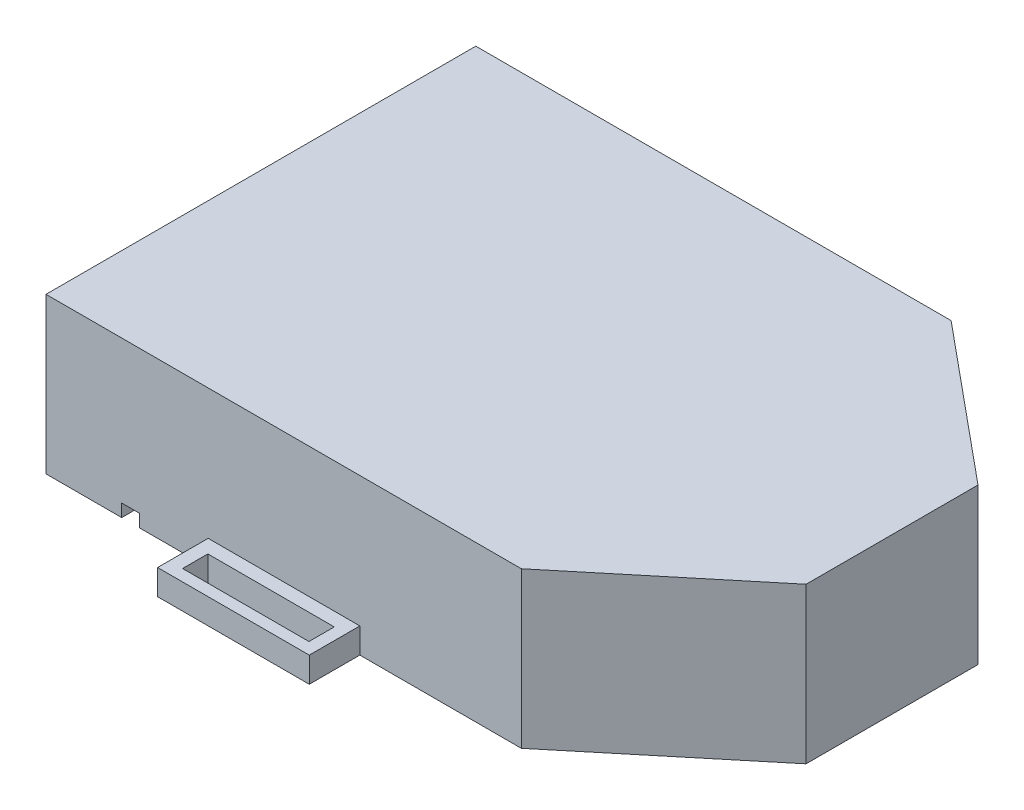
SolidWorks part; units mm, degrees
ref_plane "Front Plane" through (0, 0, 0) normal (0, 0, 1) x (1, 0, 0)
ref_plane "Top Plane" through (0, 0, 0) normal (0, 1, 0) x (1, 0, 0)
ref_plane "Right Plane" through (0, 0, 0) normal (1, 0, 0) x (0, 0, -1)
sketch "Sketch1" plane through (0, 0, 0) normal (1, 0, 0) x (0, 0, -1)
  line L23 (-43, -17.5) -> (42, -17.5)
  line L28 (-43, -17.5) -> (-43, 17.5)
  line L29 (-43, 17.5) -> (42, 17.5)
  line L30 (42, -17.5) -> (42, 17.5)
  point P0 (0, 0)
  dimension "D1" = 35
  dimension "D2" = 85
extrude "Boss-Extrude1" add sketch "Sketch1" along normal blind 145.5
sketch "Sketch4" plane through (0, 0, 0) normal (-1, 0, 0) x (0, 0, 1)
  circle A0 centre (0, 0) radius 12.75
  dimension "D1" = 25.5
extrude "Cut-Extrude2" cut sketch "Sketch4" against normal blind 55
sketch "Sketch9" plane through (0, 17.5, 0) normal (0, 1, 0) x (1, 0, 0)
  line L0 (0, 42) -> (0, -43)
  line L1 (0, -43) -> (94, -43)
  line L2 (145.5, -43) -> (0, -43) construction
  line L3 (94, -43) -> (124.818, -17.5)
  line L4 (124.818, -17.5) -> (124.818, 16.5)
  line L5 (124.818, 16.5) -> (94, 42)
  line L6 (145.5, 42) -> (0, 42) construction
  line L7 (94, 42) -> (0, 42)
  line L8 (94, 42) -> (145.5, 42)
  line L9 (145.5, 42) -> (145.5, -43)
  line L10 (145.5, -43) -> (94, -43)
  line M8 (0, -43) -> (145.5, -43)
  line M9 (145.5, -43) -> (145.5, 42)
  line M10 (145.5, 42) -> (0, 42)
  dimension "D1" = 94
  dimension "D2" = 94
  dimension "D3" = 34
  dimension "D4" = 40
  dimension "44" = 40
extrude "Cut-Extrude3" cut sketch "Sketch9" against normal through all contours L5 L4 L3 M8 M9 M10
sketch "Sketch11" plane through (0, -17.5, 0) normal (0, -1, 0) x (1, 0, 0)
  line L0 (0, -12.75) -> (55, -12.75) construction
  line L1 (55, 12.75) -> (43, 12.75)
  line L2 (55, 12.75) -> (55, -12.75)
  line L3 (55, -12.75) -> (43, -12.75)
  line L4 (43, 12.75) -> (43, -12.75)
  dimension "D1" = 12
extrude "Cut-Extrude5" cut sketch "Sketch11" against normal blind 10
sketch "Sketch12" plane through (0, -17.5, 0) normal (0, -1, 0) x (1, 0, 0)
  line L7 (48.7846, 39.5274) -> (18.4738, 39.5274)
  line L12 (94, 43) -> (0, 43) construction
  line L14 (47.4745, 10.9894) -> (50.9745, 10.9894)
  line L15 (47.4745, 36.0861) -> (14.9738, 36.0861)
  line L16 (47.4745, 10.9894) -> (47.4745, 36.0861)
  line L18 (50.9745, 10.9894) -> (50.9745, 39.5274)
  line L21 (14.9738, 39.5274) -> (14.9738, 36.0861)
  line L23 (14.9738, 39.5274) -> (14.9738, 43)
  line L24 (14.9738, 43) -> (18.4738, 43)
  line L25 (18.4738, 39.5274) -> (18.4738, 43)
  line L26 (50.9745, 36.0861) -> (50.9745, 39.5274)
  line L27 (50.9745, 39.5274) -> (48.7846, 39.5274)
  point P0 (21.5, 0)
  point P7 (49, 26.1387)
  line M8 (43, 12.75) -> (55, 12.75)
  line M15 (94, 43) -> (0, 43)
  dimension "D1" = 3.5
extrude "Cut-Extrude6" cut sketch "Sketch12" against normal blind 2.5 contours L18 L27 L7 L25 L23 L21 L15 L16 M15 M8
sketch "Sketch14" plane through (0, -17.5, 0) normal (0, -1, 0) x (1, 0, 0)
  line L0 (0, 0.5) -> (124.818, 0.5) construction
  line L10 (32.0677, -52) -> (62.0677, -52)
  line L12 (34.7077, -44.7022) -> (59.7077, -44.7022)
  line L13 (0, 43) -> (0, -42) construction
  line L14 (94, -42) -> (0, -42) construction
  line L15 (32.0677, -52) -> (32.0677, -42)
  line L16 (32.0677, -42) -> (62.0677, -42)
  line L17 (62.0677, -52) -> (62.0677, -42)
  line L18 (34.7077, -44.7022) -> (34.7077, -49.7022)
  line L19 (34.7077, -49.7022) -> (59.7077, -49.7022)
  line L20 (59.7077, -44.7022) -> (59.7077, -49.7022)
  line L21 (34.7077, -44.7022) -> (59.7077, -49.7022) construction
  line L22 (34.7077, -49.7022) -> (59.7077, -44.7022) construction
  line L23 (124.818, 17.5) -> (124.818, -16.5) construction
  line L24 (32.0677, 43) -> (62.0677, 43)
  line L25 (62.0677, 53) -> (62.0677, 43)
  line L26 (32.0677, 53) -> (62.0677, 53)
  line L27 (32.0677, 53) -> (32.0677, 43)
  line L28 (34.7077, 50.7022) -> (59.7077, 50.7022)
  line L29 (59.7077, 45.7022) -> (59.7077, 50.7022)
  line L30 (34.7077, 45.7022) -> (59.7077, 45.7022)
  line L31 (34.7077, 45.7022) -> (34.7077, 50.7022)
  point P0 (47.2077, -47.2022)
  dimension "D1" = 10
  dimension "D2" = 5
  dimension "D3" = 30
  dimension "D4" = 25
extrude "Boss-Extrude2" add sketch "Sketch14" against normal blind 5
sketch "Sketch16" plane through (0, 0, 0) normal (-1, 0, 0) x (0, 0, 1)
  line L0 (-42, -17.5) -> (-42, 17.5)
  line L1 (-42, 17.5) -> (43, 17.5)
  line L2 (43, 17.5) -> (43, -17.5)
  line L3 (43, -17.5) -> (-42, -17.5)
  line L4 (-42, 13.2604) -> (43, 13.2604)
  line L5 (0.141, -12.7508) -> (-0.1518, -12.7491)
  circle A0 centre (0, 0) radius 12.75
  point P15 (0, 0)
  line M8 (-42, 17.5) -> (-42, -17.5)
  line M11 (43, 17.5) -> (-42, 17.5)
extrude "Cut-Extrude12" cut sketch "Sketch16" against normal up to next contours L4 L2 M8 M11
